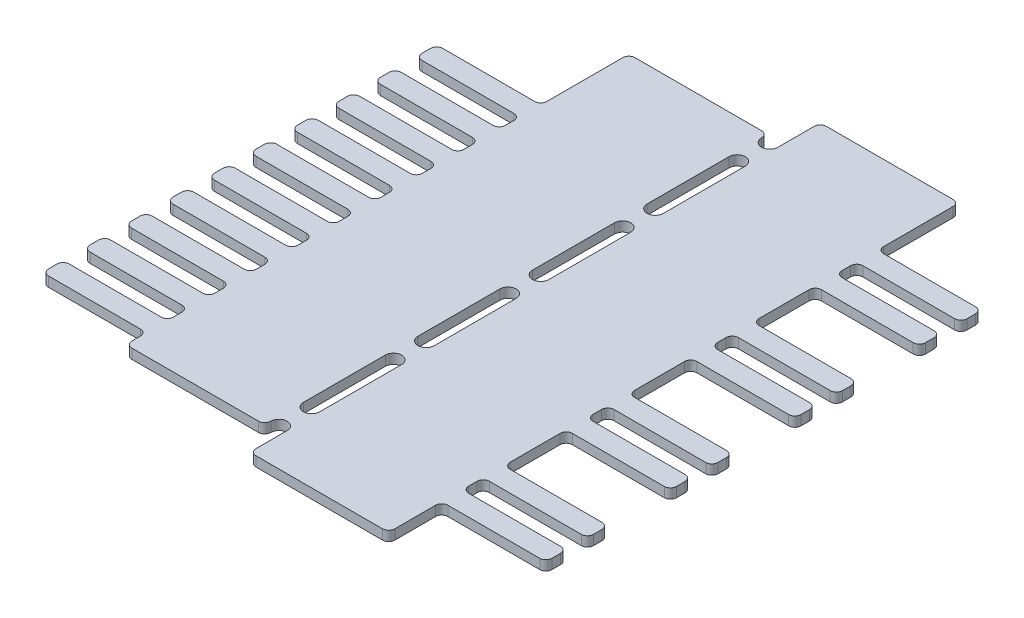
SolidWorks part; units mm, degrees
ref_plane "Front Plane" through (0, 0, 0) normal (0, 0, 1) x (1, 0, 0)
ref_plane "Top Plane" through (0, 0, 0) normal (0, 1, 0) x (1, 0, 0)
ref_plane "Right Plane" through (0, 0, 0) normal (1, 0, 0) x (0, 0, -1)
sketch "Sketch1" plane through (0, 0, 0) normal (0, 1, 0) x (1, 0, 0)
  line L0 (-0.75, 10) -> (-12, 10)
  line L2 (0, 9.25) -> (0, 0.75)
  line L5 (-12.75, 11.27) -> (0, 11.27) construction
  line L7 (-12.75, 10.75) -> (-12.75, 11.79)
  line L8 (-12, 12.54) -> (-0.75, 12.54)
  line L12 (0, 14.33) -> (0, 13.29)
  line L17 (-0.75, 15.08) -> (-12, 15.08)
  line L22 (-12.75, 15.83) -> (-12.75, 16.87)
  line L27 (-12, 17.62) -> (-0.75, 17.62)
  line L56 (16.25, 0) -> (0.75, 0)
  line L84 (0, 19.41) -> (0, 10.91) [skipped]
  line L85 (-0.75, 20.16) -> (-12, 20.16) [skipped]
  line L86 (-12.75, 20.91) -> (-12.75, 21.95) [skipped]
  line L87 (-12, 22.7) -> (-0.75, 22.7) [skipped]
  line L88 (0, 24.49) -> (0, 15.99) [skipped]
  line L89 (-0.75, 25.24) -> (-12, 25.24) [skipped]
  line L90 (-12.75, 25.99) -> (-12.75, 27.03) [skipped]
  line L91 (-12, 27.78) -> (-0.75, 27.78) [skipped]
  line L92 (0, 29.57) -> (0, 21.07) [skipped]
  line L93 (-0.75, 30.32) -> (-12, 30.32) [skipped]
  line L94 (-12.75, 31.07) -> (-12.75, 32.11) [skipped]
  line L95 (-12, 32.86) -> (-0.75, 32.86) [skipped]
  line L96 (0, 34.65) -> (0, 26.15) [skipped]
  line L97 (-0.75, 35.4) -> (-12, 35.4) [skipped]
  line L98 (-12.75, 36.15) -> (-12.75, 37.19) [skipped]
  line L99 (-12, 37.94) -> (-0.75, 37.94) [skipped]
  line L100 (0, 39.73) -> (0, 31.23) [skipped]
  line L101 (-0.75, 40.48) -> (-12, 40.48) [skipped]
  line L102 (-12.75, 41.23) -> (-12.75, 42.27) [skipped]
  line L103 (-12, 43.02) -> (-0.75, 43.02) [skipped]
  line L104 (0, 44.81) -> (0, 36.31) [skipped]
  line L105 (-0.75, 45.56) -> (-12, 45.56) [skipped]
  line L106 (-12.75, 46.31) -> (-12.75, 47.35) [skipped]
  line L107 (-12, 48.1) -> (-0.75, 48.1) [skipped]
  line L108 (0, 49.89) -> (0, 41.39) [skipped]
  line L109 (-0.75, 50.64) -> (-12, 50.64) [skipped]
  line L110 (-12.75, 51.39) -> (-12.75, 52.43) [skipped]
  line L111 (-12, 53.18) -> (-0.75, 53.18) [skipped]
  line L112 (0, 54.97) -> (0, 46.47) [skipped]
  line L113 (-0.75, 55.72) -> (-12, 55.72) [skipped]
  line L114 (-12.75, 56.47) -> (-12.75, 57.51) [skipped]
  line L115 (-12, 58.26) -> (-0.75, 58.26) [skipped]
  line L116 (-0.75, 25.24) -> (-12, 25.24)
  line L117 (-12.75, 25.99) -> (-12.75, 27.03)
  line L118 (-12, 27.78) -> (-0.75, 27.78)
  line L119 (0, 29.57) -> (0, 28.53)
  line L120 (-0.75, 30.32) -> (-12, 30.32)
  line L121 (-12.75, 31.07) -> (-12.75, 32.11)
  line L122 (-12, 32.86) -> (-0.75, 32.86)
  line L123 (-0.75, 40.48) -> (-12, 40.48)
  line L124 (-12.75, 41.23) -> (-12.75, 42.27)
  line L125 (-12, 43.02) -> (-0.75, 43.02)
  line L126 (0, 44.81) -> (0, 43.77)
  line L127 (-0.75, 45.56) -> (-12, 45.56)
  line L128 (-12.75, 46.31) -> (-12.75, 47.35)
  line L129 (-12, 48.1) -> (-0.75, 48.1)
  line L130 (-0.75, 55.72) -> (-12, 55.72)
  line L131 (-12.75, 56.47) -> (-12.75, 57.51)
  line L132 (-12, 58.26) -> (-0.75, 58.26)
  line L133 (0, 60.05) -> (0, 59.01)
  line L134 (-0.75, 60.8) -> (-12, 60.8)
  line L135 (-12.75, 61.55) -> (-12.75, 62.59)
  line L136 (-12, 63.34) -> (-0.75, 63.34)
  line L137 (0, 24.49) -> (0, 18.37)
  line L138 (0, 33.61) -> (0, 39.73)
  line L139 (0, 48.85) -> (0, 54.97)
  line L140 (0, 64.09) -> (0, 69.09)
  line L141 (0.75, 69.84) -> (16.25, 69.84)
  line L145 (36.75, 15.2205) -> (48, 15.2205)
  line L157 (36, 14.4705) -> (36, 5.183)
  line L158 (35.25, 4.433) -> (19.75, 4.433)
  line L160 (19.75, 66.0205) -> (35.25, 66.0205)
  line L188 (18, 5.183) -> (18, 56.2098) construction
  line L190 (17, 0.75) -> (17, 5.183)
  line L191 (19, 5.183) -> (18, 5.183) construction
  line L192 (19, 65.2705) -> (18, 65.2705) construction
  line L193 (18.5, 56.7098) -> (18.5, 60.84) construction
  line L194 (17.5, 60.84) -> (17.5, 56.7098) construction
  line L195 (17, 65.2705) -> (17, 69.09)
  line L196 (18, 56.2098) -> (18, 57.2098) construction
  line L197 (18, 57.2098) -> (18, 60.34) construction
  line L198 (18, 60.34) -> (18, 61.34) construction
  line L199 (18, 61.34) -> (18, 65.2705) construction
  line L200 (48.75, 15.9705) -> (48.75, 17.0105)
  line L201 (48, 17.7605) -> (36.75, 17.7605)
  line L202 (36, 18.5105) -> (36, 19.5505)
  line L204 (48.75, 21.0505) -> (48.75, 22.0905)
  line L205 (48, 22.8405) -> (36.75, 22.8405)
  line L206 (36, 23.5905) -> (36, 24.6305)
  line L207 (36.75, 20.3005) -> (48, 20.3005)
  line L208 (48.75, 26.1305) -> (48.75, 27.1705)
  line L209 (48, 27.9205) -> (36.75, 27.9205)
  line L210 (36, 28.6705) -> (36, 29.7105)
  line L212 (18, 65.2705) -> (17, 65.2705) construction
  line L213 (18, 65.2705) -> (18, 59.9038) construction
  line L214 (36.75, 25.3805) -> (48, 25.3805)
  line L215 (48.75, 31.2105) -> (48.75, 32.2505)
  line L216 (48, 33.0005) -> (36.75, 33.0005)
  line L217 (36, 33.7505) -> (36, 34.7905)
  line L218 (18, 5.183) -> (17, 5.183) construction
  line L219 (36.75, 30.4605) -> (48, 30.4605)
  line L220 (48.75, 36.2905) -> (48.75, 37.3305)
  line L221 (48, 38.0805) -> (36.75, 38.0805)
  line L222 (36, 38.8305) -> (36, 39.8705)
  line L223 (36.75, 35.5405) -> (48, 35.5405)
  line L224 (48.75, 41.3705) -> (48.75, 42.4105)
  line L225 (48, 43.1605) -> (36.75, 43.1605)
  line L226 (36, 43.9105) -> (36, 44.9505)
  line L227 (36.75, 40.6205) -> (48, 40.6205)
  line L228 (48.75, 46.4505) -> (48.75, 47.4905)
  line L229 (48, 48.2405) -> (36.75, 48.2405)
  line L230 (36, 48.9905) -> (36, 50.0305)
  line L231 (36.75, 45.7005) -> (48, 45.7005)
  line L232 (48.75, 51.5305) -> (48.75, 52.5705)
  line L233 (48, 53.3205) -> (36.75, 53.3205)
  line L234 (36, 54.0705) -> (36, 55.1105)
  line L235 (36.75, 50.7805) -> (48, 50.7805)
  line L236 (48.75, 56.6105) -> (48.75, 57.6505)
  line L237 (48, 58.4005) -> (36.75, 58.4005)
  line L238 (36, 59.1505) -> (36, 60.1905)
  line L239 (36.75, 55.8605) -> (48, 55.8605)
  line L240 (48.75, 61.6905) -> (48.75, 62.7305)
  line L241 (48, 63.4805) -> (36.75, 63.4805)
  line L242 (36, 64.2305) -> (36, 65.2705)
  line L243 (36.75, 60.9405) -> (48, 60.9405)
  arc A0 (-0.75, 12.54) -> (0, 13.29) centre (-0.75, 13.29) ccw
  arc A1 (-12.75, 11.79) -> (-12, 12.54) centre (-12, 11.79) cw
  arc A2 (-12, 10) -> (-12.75, 10.75) centre (-12, 10.75) cw
  arc A3 (0, 0.75) -> (0.75, 0) centre (0.75, 0.75) ccw
  arc A4 (-0.75, 10) -> (0, 9.25) centre (-0.75, 9.25) cw
  arc A5 (17, 0.75) -> (16.25, 0) centre (16.25, 0.75) cw
  arc A6 (-0.75, 15.08) -> (0, 14.33) centre (-0.75, 14.33) cw
  arc A7 (-12, 15.08) -> (-12.75, 15.83) centre (-12, 15.83) cw
  arc A8 (-12.75, 16.87) -> (-12, 17.62) centre (-12, 16.87) cw
  arc A9 (-0.75, 17.62) -> (0, 18.37) centre (-0.75, 18.37) ccw
  arc A44 (-0.75, 20.16) -> (0, 19.41) centre (-0.75, 19.41) cw [skipped]
  arc A45 (-12, 20.16) -> (-12.75, 20.91) centre (-12, 20.91) cw [skipped]
  arc A46 (-12.75, 21.95) -> (-12, 22.7) centre (-12, 21.95) cw [skipped]
  arc A47 (-0.75, 22.7) -> (0, 23.45) centre (-0.75, 23.45) ccw [skipped]
  arc A48 (-0.75, 25.24) -> (0, 24.49) centre (-0.75, 24.49) cw [skipped]
  arc A49 (-12, 25.24) -> (-12.75, 25.99) centre (-12, 25.99) cw [skipped]
  arc A50 (-12.75, 27.03) -> (-12, 27.78) centre (-12, 27.03) cw [skipped]
  arc A51 (-0.75, 27.78) -> (0, 28.53) centre (-0.75, 28.53) ccw [skipped]
  arc A52 (-0.75, 30.32) -> (0, 29.57) centre (-0.75, 29.57) cw [skipped]
  arc A53 (-12, 30.32) -> (-12.75, 31.07) centre (-12, 31.07) cw [skipped]
  arc A54 (-12.75, 32.11) -> (-12, 32.86) centre (-12, 32.11) cw [skipped]
  arc A55 (-0.75, 32.86) -> (0, 33.61) centre (-0.75, 33.61) ccw [skipped]
  arc A56 (-0.75, 35.4) -> (0, 34.65) centre (-0.75, 34.65) cw [skipped]
  arc A57 (-12, 35.4) -> (-12.75, 36.15) centre (-12, 36.15) cw [skipped]
  arc A58 (-12.75, 37.19) -> (-12, 37.94) centre (-12, 37.19) cw [skipped]
  arc A59 (-0.75, 37.94) -> (0, 38.69) centre (-0.75, 38.69) ccw [skipped]
  arc A60 (-0.75, 40.48) -> (0, 39.73) centre (-0.75, 39.73) cw [skipped]
  arc A61 (-12, 40.48) -> (-12.75, 41.23) centre (-12, 41.23) cw [skipped]
  arc A62 (-12.75, 42.27) -> (-12, 43.02) centre (-12, 42.27) cw [skipped]
  arc A63 (-0.75, 43.02) -> (0, 43.77) centre (-0.75, 43.77) ccw [skipped]
  arc A64 (-0.75, 45.56) -> (0, 44.81) centre (-0.75, 44.81) cw [skipped]
  arc A65 (-12, 45.56) -> (-12.75, 46.31) centre (-12, 46.31) cw [skipped]
  arc A66 (-12.75, 47.35) -> (-12, 48.1) centre (-12, 47.35) cw [skipped]
  arc A67 (-0.75, 48.1) -> (0, 48.85) centre (-0.75, 48.85) ccw [skipped]
  arc A68 (-0.75, 50.64) -> (0, 49.89) centre (-0.75, 49.89) cw [skipped]
  arc A69 (-12, 50.64) -> (-12.75, 51.39) centre (-12, 51.39) cw [skipped]
  arc A70 (-12.75, 52.43) -> (-12, 53.18) centre (-12, 52.43) cw [skipped]
  arc A71 (-0.75, 53.18) -> (0, 53.93) centre (-0.75, 53.93) ccw [skipped]
  arc A72 (-0.75, 55.72) -> (0, 54.97) centre (-0.75, 54.97) cw [skipped]
  arc A73 (-12, 55.72) -> (-12.75, 56.47) centre (-12, 56.47) cw [skipped]
  arc A74 (-12.75, 57.51) -> (-12, 58.26) centre (-12, 57.51) cw [skipped]
  arc A75 (-0.75, 58.26) -> (0, 59.01) centre (-0.75, 59.01) ccw [skipped]
  arc A76 (-0.75, 27.78) -> (0, 28.53) centre (-0.75, 28.53) ccw
  arc A77 (-12.75, 27.03) -> (-12, 27.78) centre (-12, 27.03) cw
  arc A78 (-12, 25.24) -> (-12.75, 25.99) centre (-12, 25.99) cw
  arc A79 (-0.75, 25.24) -> (0, 24.49) centre (-0.75, 24.49) cw
  arc A80 (-0.75, 30.32) -> (0, 29.57) centre (-0.75, 29.57) cw
  arc A81 (-12, 30.32) -> (-12.75, 31.07) centre (-12, 31.07) cw
  arc A82 (-12.75, 32.11) -> (-12, 32.86) centre (-12, 32.11) cw
  arc A83 (-0.75, 32.86) -> (0, 33.61) centre (-0.75, 33.61) ccw
  arc A84 (-0.75, 43.02) -> (0, 43.77) centre (-0.75, 43.77) ccw
  arc A85 (-12.75, 42.27) -> (-12, 43.02) centre (-12, 42.27) cw
  arc A86 (-12, 40.48) -> (-12.75, 41.23) centre (-12, 41.23) cw
  arc A87 (-0.75, 40.48) -> (0, 39.73) centre (-0.75, 39.73) cw
  arc A88 (-0.75, 45.56) -> (0, 44.81) centre (-0.75, 44.81) cw
  arc A89 (-12, 45.56) -> (-12.75, 46.31) centre (-12, 46.31) cw
  arc A90 (-12.75, 47.35) -> (-12, 48.1) centre (-12, 47.35) cw
  arc A91 (-0.75, 48.1) -> (0, 48.85) centre (-0.75, 48.85) ccw
  arc A92 (-0.75, 58.26) -> (0, 59.01) centre (-0.75, 59.01) ccw
  arc A93 (-12.75, 57.51) -> (-12, 58.26) centre (-12, 57.51) cw
  arc A94 (-12, 55.72) -> (-12.75, 56.47) centre (-12, 56.47) cw
  arc A95 (-0.75, 55.72) -> (0, 54.97) centre (-0.75, 54.97) cw
  arc A96 (-0.75, 60.8) -> (0, 60.05) centre (-0.75, 60.05) cw
  arc A97 (-12, 60.8) -> (-12.75, 61.55) centre (-12, 61.55) cw
  arc A98 (-12.75, 62.59) -> (-12, 63.34) centre (-12, 62.59) cw
  arc A99 (-0.75, 63.34) -> (0, 64.09) centre (-0.75, 64.09) ccw
  arc A100 (0, 69.09) -> (0.75, 69.84) centre (0.75, 69.09) cw
  arc A101 (16.25, 69.84) -> (17, 69.09) centre (16.25, 69.09) cw
  arc A107 (19, 65.2705) -> (19.75, 66.0205) centre (19.75, 65.2705) cw
  arc A144 (36, 5.183) -> (35.25, 4.433) centre (35.25, 5.183) cw
  arc A145 (19.75, 4.433) -> (19, 5.183) centre (19.75, 5.183) cw
  arc A147 (19, 5.183) -> (17, 5.183) centre (18, 5.183) ccw
  arc A148 (17, 5.183) -> (19, 5.183) centre (18, 5.183) ccw construction
  arc A149 (18.5, 60.84) -> (17.5, 60.84) centre (18, 60.84) ccw construction
  arc A150 (17.5, 56.7098) -> (18.5, 56.7098) centre (18, 56.7098) ccw construction
  arc A151 (18, 57.2098) -> (17.5, 56.7098) centre (18, 56.7098) ccw construction
  arc A152 (18.5, 56.7098) -> (18, 57.2098) centre (18, 56.7098) ccw construction
  arc A153 (18, 60.34) -> (18.5, 60.84) centre (18, 60.84) ccw construction
  arc A154 (17.5, 60.84) -> (18, 60.34) centre (18, 60.84) ccw construction
  arc A155 (17, 65.2705) -> (19, 65.2705) centre (18, 65.2705) ccw
  arc A156 (19, 65.2705) -> (17, 65.2705) centre (18, 65.2705) ccw construction
  arc A157 (36.75, 17.7605) -> (36, 18.5105) centre (36.75, 18.5105) cw
  arc A158 (48.75, 17.0105) -> (48, 17.7605) centre (48, 17.0105) ccw
  arc A159 (48, 15.2205) -> (48.75, 15.9705) centre (48, 15.9705) ccw
  arc A160 (36, 14.4705) -> (36.75, 15.2205) centre (36.75, 14.4705) cw
  arc A161 (36.75, 22.8405) -> (36, 23.5905) centre (36.75, 23.5905) cw
  arc A162 (48.75, 22.0905) -> (48, 22.8405) centre (48, 22.0905) ccw
  arc A163 (48, 20.3005) -> (48.75, 21.0505) centre (48, 21.0505) ccw
  arc A164 (36, 19.5505) -> (36.75, 20.3005) centre (36.75, 19.5505) cw
  arc A165 (36.75, 27.9205) -> (36, 28.6705) centre (36.75, 28.6705) cw
  arc A166 (48.75, 27.1705) -> (48, 27.9205) centre (48, 27.1705) ccw
  arc A167 (48, 25.3805) -> (48.75, 26.1305) centre (48, 26.1305) ccw
  arc A168 (36, 24.6305) -> (36.75, 25.3805) centre (36.75, 24.6305) cw
  arc A169 (36.75, 33.0005) -> (36, 33.7505) centre (36.75, 33.7505) cw
  arc A170 (48.75, 32.2505) -> (48, 33.0005) centre (48, 32.2505) ccw
  arc A171 (48, 30.4605) -> (48.75, 31.2105) centre (48, 31.2105) ccw
  arc A172 (36, 29.7105) -> (36.75, 30.4605) centre (36.75, 29.7105) cw
  arc A173 (36.75, 38.0805) -> (36, 38.8305) centre (36.75, 38.8305) cw
  arc A174 (48.75, 37.3305) -> (48, 38.0805) centre (48, 37.3305) ccw
  arc A175 (48, 35.5405) -> (48.75, 36.2905) centre (48, 36.2905) ccw
  arc A176 (36, 34.7905) -> (36.75, 35.5405) centre (36.75, 34.7905) cw
  arc A177 (36.75, 43.1605) -> (36, 43.9105) centre (36.75, 43.9105) cw
  arc A178 (48.75, 42.4105) -> (48, 43.1605) centre (48, 42.4105) ccw
  arc A179 (48, 40.6205) -> (48.75, 41.3705) centre (48, 41.3705) ccw
  arc A180 (36, 39.8705) -> (36.75, 40.6205) centre (36.75, 39.8705) cw
  arc A181 (36.75, 48.2405) -> (36, 48.9905) centre (36.75, 48.9905) cw
  arc A182 (48.75, 47.4905) -> (48, 48.2405) centre (48, 47.4905) ccw
  arc A183 (48, 45.7005) -> (48.75, 46.4505) centre (48, 46.4505) ccw
  arc A184 (36, 44.9505) -> (36.75, 45.7005) centre (36.75, 44.9505) cw
  arc A185 (36.75, 53.3205) -> (36, 54.0705) centre (36.75, 54.0705) cw
  arc A186 (48.75, 52.5705) -> (48, 53.3205) centre (48, 52.5705) ccw
  arc A187 (48, 50.7805) -> (48.75, 51.5305) centre (48, 51.5305) ccw
  arc A188 (36, 50.0305) -> (36.75, 50.7805) centre (36.75, 50.0305) cw
  arc A189 (36.75, 58.4005) -> (36, 59.1505) centre (36.75, 59.1505) cw
  arc A190 (48.75, 57.6505) -> (48, 58.4005) centre (48, 57.6505) ccw
  arc A191 (48, 55.8605) -> (48.75, 56.6105) centre (48, 56.6105) ccw
  arc A192 (36, 55.1105) -> (36.75, 55.8605) centre (36.75, 55.1105) cw
  arc A193 (36.75, 63.4805) -> (36, 64.2305) centre (36.75, 64.2305) cw
  arc A194 (48.75, 62.7305) -> (48, 63.4805) centre (48, 62.7305) ccw
  arc A195 (48, 60.9405) -> (48.75, 61.6905) centre (48, 61.6905) ccw
  arc A196 (36, 60.1905) -> (36.75, 60.9405) centre (36.75, 60.1905) cw
  arc A197 (36, 65.2705) -> (35.25, 66.0205) centre (35.25, 65.2705) ccw
  point P0 (0, 0)
  point P48 (-12.75, 12.54)
  point P69 (-12.75, 10)
  point P78 (0, 0)
  point P81 (0, 10)
  point P132 (27.5, 4.433)
  point P390 (42.375, 15.2205)
  dimension "D6" = 0.75
  dimension "D7" = 0.75
  dimension "D8" = 4
  dimension "D9" = 10.16
  dimension "D11" = 0.75
  dimension "D13" = 4.433
  dimension "D14" = 0.75
  dimension "D15" = 9
  dimension "D16" = 0.75
  dimension "D12" = 6.5
  dimension "D21" = 0.75
  dimension "D22" = 17
  dimension "D5" = 2
  dimension "D24" = 4.1302
  dimension "D25" = 17
  dimension "D17" = 0.75
  dimension "D1" = 2.54
  dimension "D2" = 12
  dimension "D3" = 10
  dimension "D4" = 10
  dimension "D10" = 5.08
  dimension "D18" = 10
  dimension "D19" = 12
  dimension "D20" = 2.54
  dimension "D23" = 5.08
  dimension "D26" = 10.7875
  dimension "D27" = 69.84
  dimension "D28" = 3.8195
  dimension "D29" = 3.8195
extrude "Boss-Extrude1" add sketch "Sketch1" along normal blind 1.2
sketch "Sketch2" plane through (0, 0, 0) normal (0, -1, 0) x (1, 0, 0)
  line L0 (18, -5.183) -> (18, -65.2705) construction
  line L1 (18, -61.2705) -> (18, -51.2505) construction
  line L2 (17, -61.2705) -> (17, -51.2505)
  line L3 (19, -61.2705) -> (19, -51.2505)
  line L4 (18, -35.2268) -> (0, -35.2268) construction
  line L5 (0, -39.73) -> (0, -33.61) construction
  line L6 (18, -47.2505) -> (18, -37.2305) construction
  line L7 (17, -47.2505) -> (17, -37.2305)
  line L8 (19, -47.2505) -> (19, -37.2305)
  line L9 (18, -23.203) -> (18, -33.223) construction
  line L10 (17, -23.203) -> (17, -33.223)
  line L11 (19, -23.203) -> (19, -33.223)
  line L12 (18, -9.183) -> (18, -19.203) construction
  line L13 (17, -9.183) -> (17, -19.203)
  line L14 (19, -9.183) -> (19, -19.203)
  arc A0 (17, -61.2705) -> (19, -61.2705) centre (18, -61.2705) ccw
  arc A1 (19, -51.2505) -> (17, -51.2505) centre (18, -51.2505) ccw
  circle A2 centre (18, -65.2705) radius 1 construction
  arc A3 (19, -65.2705) -> (17, -65.2705) centre (18, -65.2705) ccw construction
  arc A4 (17, -47.2505) -> (19, -47.2505) centre (18, -47.2505) ccw
  arc A5 (19, -37.2305) -> (17, -37.2305) centre (18, -37.2305) ccw
  arc A6 (17, -23.203) -> (19, -23.203) centre (18, -23.203) cw
  arc A7 (19, -33.223) -> (17, -33.223) centre (18, -33.223) cw
  arc A8 (17, -9.183) -> (19, -9.183) centre (18, -9.183) cw
  arc A9 (19, -19.203) -> (17, -19.203) centre (18, -19.203) cw
  point P6 (18, -56.2605)
  point P23 (18, -42.2405)
  point P28 (18, -28.213)
  point P35 (18, -14.193)
  dimension "D4" = 4
  dimension "D1" = 10.02
  dimension "D2" = 4
  dimension "D3" = 2
extrude "Cut-Extrude1" cut sketch "Sketch2" against normal through all
move or copy body "Body-Move/Copy1" bodies to move or copy 102 copy no rotation origin (17.625, 0, -34.92) rotation axis (0, 1, 0) rotation angle 180
equation "\"T\"= 1"
